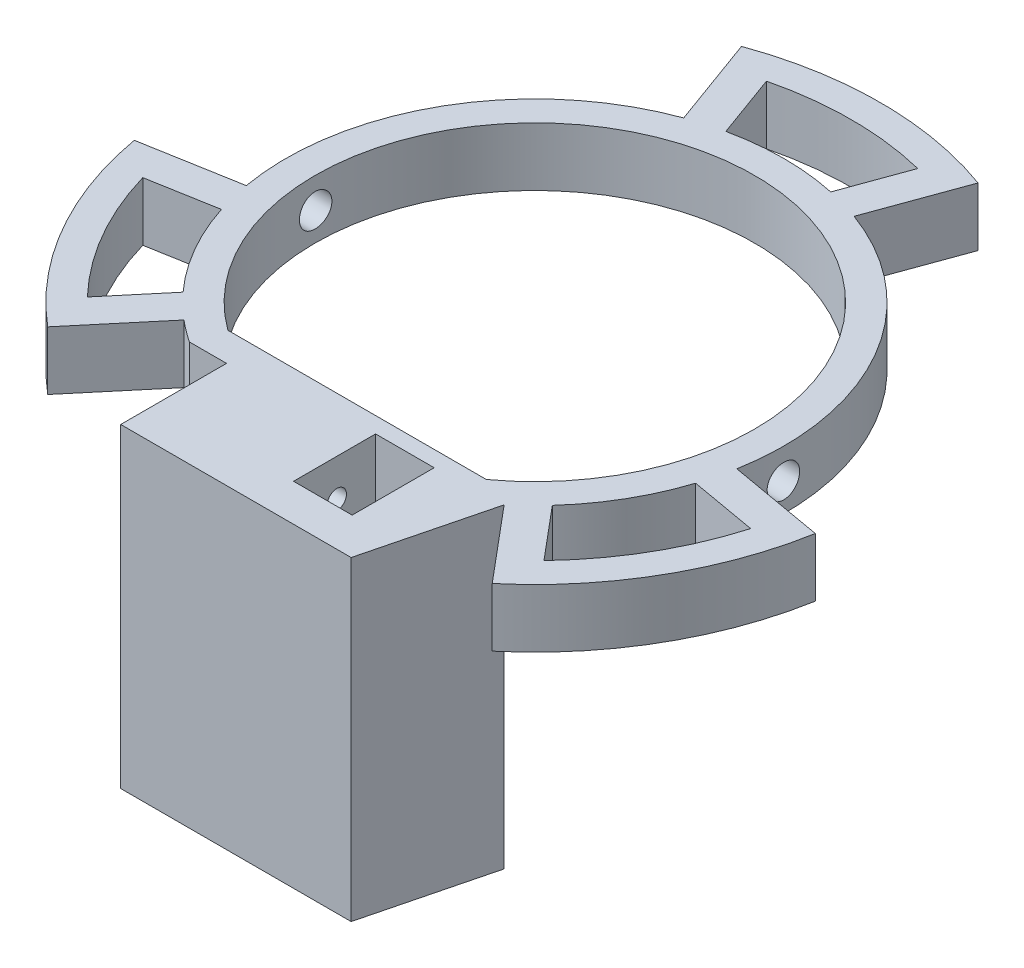
SolidWorks part; units mm, degrees
ref_plane "Front Plane" through (0, 0, 0) normal (0, 0, 1) x (1, 0, 0)
ref_plane "Top Plane" through (0, 0, 0) normal (0, 1, 0) x (1, 0, 0)
ref_plane "Right Plane" through (0, 0, 0) normal (1, 0, 0) x (0, 0, -1)
sketch "Sketch1" plane through (0, 0, 0) normal (0, 1, 0) x (1, 0, 0)
  line L0 (-26.9875, 0) -> (-23.8125, 0)
  line L1 (-25.6893, -8.2695) -> (-32.9342, -9.547)
  line L2 (-24.082, -28.6999) -> (-17.3472, -20.6736)
  line L3 (-36.8958, -6.5057) -> (-26.5775, -4.6863)
  line L4 (25.6893, -8.2695) -> (32.9342, -9.547)
  line L5 (-20.0063, -18.1128) -> (-24.735, -23.7483)
  line L6 (24.082, -28.6999) -> (17.3472, -20.6736)
  line L7 (20.0063, -18.1128) -> (24.735, -23.7483)
  line L8 (36.8958, -6.5057) -> (26.5775, -4.6863)
  line L9 (-5.683, 26.3824) -> (-8.1991, 33.2953)
  line L10 (-12.8138, 35.2056) -> (-9.2303, 25.36)
  line L11 (5.683, 26.3824) -> (8.1991, 33.2953)
  line L12 (12.8138, 35.2056) -> (9.2303, 25.36)
  circle A0 centre (0, 0) radius 37.465
  circle A4 centre (0, 0) radius 34.29
  circle A5 centre (0, 0) radius 26.9875
  circle A6 centre (0, 0) radius 23.8125
extrude "Boss-Extrude1" add sketch "Sketch1" along normal blind 6.35
sketch "Sketch2" plane through (0, 0, 0) normal (0, -1, 0) x (1, 0, 0)
  line L0 (0, 26.9875) -> (0, 37.7825)
  arc A0 (17.3472, 20.6736) -> (-17.3472, 20.6736) centre (0, 0) ccw construction
sketch "Sketch4" plane through (0, 0, 0) normal (1, 0, 0) x (0, 0, -1)
  line L0 (0, 6.35) -> (0, 0) construction
  circle A0 centre (0, 3.0717) radius 1.7577
extrude "Cut-Extrude1" cut sketch "Sketch4" against normal through all both and the other way through all
sketch "Sketch5" plane through (0, 0, 0) normal (1, 0, 0) x (0, 0, -1)
  line L0 (0, 6.35) -> (0, 0) construction
  circle A0 centre (0, 3.0629) radius 1.7221
sketch "Sketch7" plane through (0, 6.35, 0) normal (0, 1, 0) x (1, 0, 0)
  line L1 (11.9401, -24.2025) -> (11.9401, -28.3123)
  line L2 (-10.9679, -24.9752) -> (-10.9679, -24.6583)
  line L3 (0, -26.9875) -> (0, -37.7825) construction
  line L5 (14.0029, -19.2602) -> (-14.0029, -19.2602)
  line L7 (-10.9679, -24.6583) -> (-10.9679, -31.4214)
  line L9 (0, -31.6834) -> (-10.9679, -31.6834)
  line L10 (-10.9679, -31.6834) -> (-10.9679, -31.4214)
  line L11 (0, -31.6834) -> (11.822, -31.6834)
  line L12 (11.9401, -28.3123) -> (11.9401, -31.6834)
  line L13 (11.9401, -31.6834) -> (11.822, -31.6834)
  circle A2 centre (0, 0) radius 23.8125
  circle A3 centre (0, 0) radius 26.9875
extrude "Boss-Extrude3" add sketch "Sketch7" against normal up to surface (6.35 mm away) up to face at (0, 0, 0)
sketch "Sketch13" plane through (0, 0, 31.6834) normal (0, 0, 1) x (1, 0, 0)
  line L0 (11.9401, 0) -> (11.9401, -27.8166)
  line L3 (-8.0619, -27.8166) -> (-10.9679, -27.8166)
  line L4 (-10.9679, -27.8166) -> (-10.9679, 6.35)
  line L5 (11.9401, -27.8166) -> (13.5479, -27.8166)
  line L7 (-8.0619, -29.4453) -> (-10.9679, -29.4453)
  line L8 (-10.9679, -29.4453) -> (11.9401, -29.4453)
  line L9 (-8.0619, -27.8166) -> (11.9401, -27.8166)
  line L10 (13.5479, -27.8166) -> (13.5479, 0)
  line L11 (11.9401, 0) -> (17.3472, 0) construction
  line L12 (13.5479, 0) -> (13.5479, -29.4453)
  line L13 (13.5479, -29.4453) -> (11.9401, -29.4453)
  line L14 (13.5479, 0) -> (13.5479, 6.35)
  line L15 (-3.9139, -23.2456) -> (11.9401, -23.2456)
  line L16 (-6.7139, -23.2456) -> (-6.4599, -23.2456)
  line L17 (-6.7139, -27.0626) -> (-6.7139, -22.7041) construction
  line L18 (-6.4599, -23.2456) -> (-6.4599, -27.8166)
  line L19 (-6.4599, -23.2456) -> (-3.9139, -23.2456)
  line L20 (13.5479, 6.35) -> (11.9401, 6.35)
  line L21 (-10.9679, -29.4453) -> (-10.9679, -27.8166)
  line L22 (-10.9679, 6.35) -> (11.9401, 6.35)
extrude "Boss-Extrude7" add sketch "Sketch13" along normal blind 2.2225
sketch "Sketch14" plane through (0, 0, 31.6834) normal (0, 0, -1) x (-1, 0, 0)
  line L1 (-11.9401, -23.2456) -> (6.4599, -23.2456)
  line L2 (-11.9401, -23.2456) -> (-11.9401, -27.8166)
  line L3 (-11.9401, -27.8166) -> (6.4599, -27.8166)
  line L4 (6.4599, -23.2456) -> (6.4599, -27.8166)
extrude "Boss-Extrude8" add sketch "Sketch14" along normal up to surface (12.4233 mm away) up to face at (0, 3.175, 19.2602)
sketch "Sketch19" plane through (0, 0, 31.6834) normal (0, 0, -1) x (-1, 0, 0)
  line L1 (-11.9401, -27.8166) -> (-13.5479, -27.8166)
  line L2 (-11.9401, -27.8166) -> (-11.9401, 6.35)
  line L3 (-11.9401, 6.35) -> (-13.5479, 6.35)
  line L4 (-13.5479, -27.8166) -> (-13.5479, 6.35)
extrude "Boss-Extrude14" add sketch "Sketch19" along normal up to surface (12.4233 mm away) up to face at (0, 3.175, 19.2602)
sketch "Sketch20" plane through (13.5479, 0, 0) normal (1, 0, 0) x (0, 0, -1)
  line L1 (-19.2602, -27.8166) -> (-33.9059, -27.8166)
  line L2 (-19.2602, -27.8166) -> (-19.2602, 6.35)
  line L3 (-19.2602, 6.35) -> (-33.9059, 6.35)
  line L4 (-33.9059, -27.8166) -> (-33.9059, 6.35)
extrude "Boss-Extrude15" add sketch "Sketch20" along normal up to vertex (0.455 mm away)
sketch "Sketch21" plane through (0, 0, 0) normal (0, -1, 0) x (1, 0, 0)
  line L2 (-6.4599, 19.2602) -> (-6.4599, 31.6834) construction
  line L3 (-6.4599, 30.2998) -> (-6.4599, 19.2602)
  line L4 (-6.4599, 19.2602) -> (-6.4599, 31.6834)
  line L6 (-9.4679, 30.6294) -> (-9.4679, 31.6834)
  line L7 (-6.4599, 31.6834) -> (-10.9679, 31.6834) construction
  line L8 (-9.4679, 31.6834) -> (-9.4679, 19.2602)
  line L9 (-14.0029, 19.2602) -> (11.9401, 19.2602) construction
  line L10 (-9.4679, 19.2602) -> (-6.4599, 19.2602)
  line L11 (-9.4679, 31.6834) -> (-6.4599, 31.6834)
  line M16 (-14.0029, 19.2602) -> (11.9401, 19.2602)
  line M18 (11.9401, 31.6834) -> (-10.9679, 31.6834)
extrude "Cut-Extrude2" cut sketch "Sketch21" against normal blind 4.8895 contours L6 L8 L3 L4 M16 M18
sketch "Sketch23" plane through (-10.9679, 0, 0) normal (-1, 0, 0) x (0, 0, 1)
  circle A0 centre (25.1794, 2.2874) radius 1.0414
ref_plane "Plane1" through (-10.9679, 6.35, 33.9059) normal (0, 0, -1) x (-1, 0, 0)
sketch "Sketch25" plane through (-10.9679, 0, 0) normal (-1, 0, 0) x (0, 0, 1)
  line L1 (33.9059, 6.35) -> (22.4387, 6.35)
  line L2 (33.9059, 6.35) -> (33.9059, 0)
  line L3 (33.9059, 0) -> (22.4387, 0)
  line L4 (22.4387, 6.35) -> (22.4387, 0)
extrude "Cut-Extrude3" cut sketch "Sketch25" along normal blind 4.7625
extrude "Cut-Extrude4" cut sketch "Sketch23" against normal blind 17.78
sketch "Sketch27" plane through (-6.4599, 0, 0) normal (-1, 0, 0) x (0, 0, 1)
  circle A0 centre (25.1794, -25.2126) radius 1.0414
extrude "Cut-Extrude5" cut sketch "Sketch27" against normal blind 12.7
sketch "Sketch29" plane through (0, 6.35, 0) normal (0, 1, 0) x (1, 0, 0)
  line L1 (14.0029, -33.9059) -> (14.0029, -23.0704)
  line L2 (14.0029, -23.0704) -> (14.0029, -20.7063)
  line L5 (14.0029, -20.6736) -> (14.0029, -20.7063)
  line L6 (17.3472, -20.6736) -> (14.0029, -33.9059)
  line L7 (14.0029, -20.6736) -> (14.0029, -19.2602)
  line L11 (17.3472, -20.6736) -> (14.0029, -19.2602)
  circle A3 centre (0, 0) radius 23.8125
  line M23 (14.0029, -33.9059) -> (14.0029, -23.0704)
  arc M24 (14.0029, -23.0704) -> (17.3472, -20.6736) centre (0, 0) ccw
extrude "Boss-Extrude17" add sketch "Sketch29" against normal up to surface (34.1666 mm away) contours L11 L7 L5 L2 M24 | L6 M24 M23 up to face at (-1.1417, -27.8166, 28.2832)
sketch "Sketch30" plane through (0, 0, 19.2602) normal (0, 0, -1) x (-1, 0, 0)
  line L0 (8.8156, 4.8895) -> (8.8156, 6.35)
  line L1 (9.4679, 4.8895) -> (6.4599, 4.8895) construction
  line L2 (-14.0029, 6.35) -> (14.0029, 6.35) construction
sketch "Sketch31" plane through (0, 6.35, 0) normal (0, 1, 0) x (1, 0, 0)
  line L1 (3.7269, -20.983) -> (10.0769, -20.983)
  line L2 (3.7269, -20.983) -> (3.7269, -29.873)
  line L3 (3.7269, -29.873) -> (10.0769, -29.873)
  line L4 (10.0769, -20.983) -> (10.0769, -29.873)
  dimension "D1" = 6.35
  dimension "D2" = 8.89
extrude "Cut-Extrude6" cut sketch "Sketch31" against normal blind 7.874
